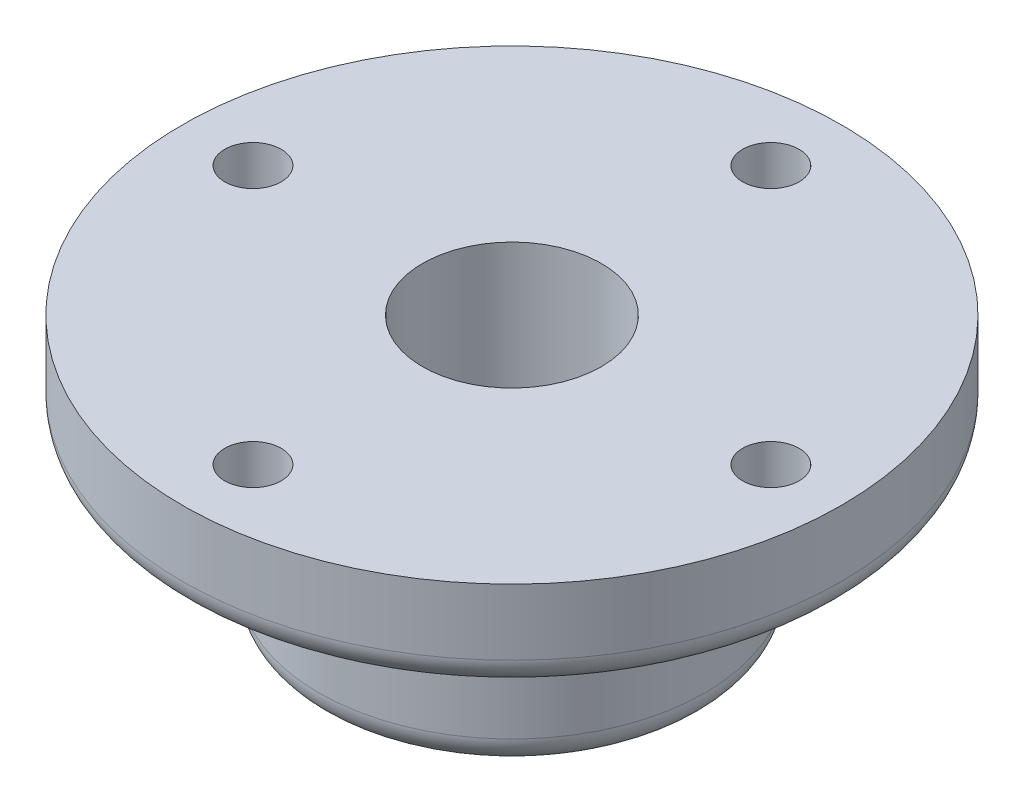
SolidWorks part; units mm, degrees
ref_plane "Front Plane" through (0, 0, 0) normal (0, 0, 1) x (1, 0, 0)
ref_plane "Top Plane" through (0, 0, 0) normal (0, 1, 0) x (1, 0, 0)
ref_plane "Right Plane" through (0, 0, 0) normal (1, 0, 0) x (0, 0, -1)
sketch "Sketch1" plane through (0, 0, 0) normal (0, 0, 1) x (1, 0, 0)
  line L0 (0, -27.5) -> (0, 27.5) construction
  line L1 (70, 27.5) -> (19, 27.5)
  line L2 (70, 27.5) -> (70, 13.5)
  line L3 (64, 7.5) -> (47, 7.5)
  line L4 (41, -21.5) -> (41, 1.5)
  line L5 (35, -27.5) -> (19, -27.5)
  line L6 (19, -27.5) -> (19, 27.5)
  arc A0 (70, 13.5) -> (64, 7.5) centre (64, 13.5) cw
  arc A1 (47, 7.5) -> (41, 1.5) centre (47, 1.5) ccw
  arc A2 (41, -21.5) -> (35, -27.5) centre (35, -21.5) cw
  point P2 (0, 0)
  point P4 (0, 0)
  point P14 (0, 0)
  point P17 (0, 0)
  dimension "D4" = 6
  dimension "D5" = 6
  dimension "D6" = 6
  dimension "D1" = 55
  dimension "D2" = 19
  dimension "D3" = 51
  dimension "D7" = 16
  dimension "D8" = 20
  dimension "D9" = 140
revolve "Revolve1" add sketch "Sketch1" angle 360 about L0
sketch "Sketch2" plane through (0, 7.5, 0) normal (0, -1, 0) x (1, 0, 0)
  circle A0 centre (0, 0) radius 55 construction
  circle A1 centre (-55, 0) radius 6
  circle A2 centre (0, 55) radius 6
  circle A3 centre (55, 0) radius 6
  circle A4 centre (0, -55) radius 6
  dimension "D1" = 110
  dimension "D2" = 12
  dimension "D3" = 12
  dimension "D4" = 12
  dimension "D5" = 12
extrude "Cut-Extrude1" cut sketch "Sketch2" against normal through all
equation "\"r\"=7.76208"
equation "\"D5@Sketch1\"=6"
